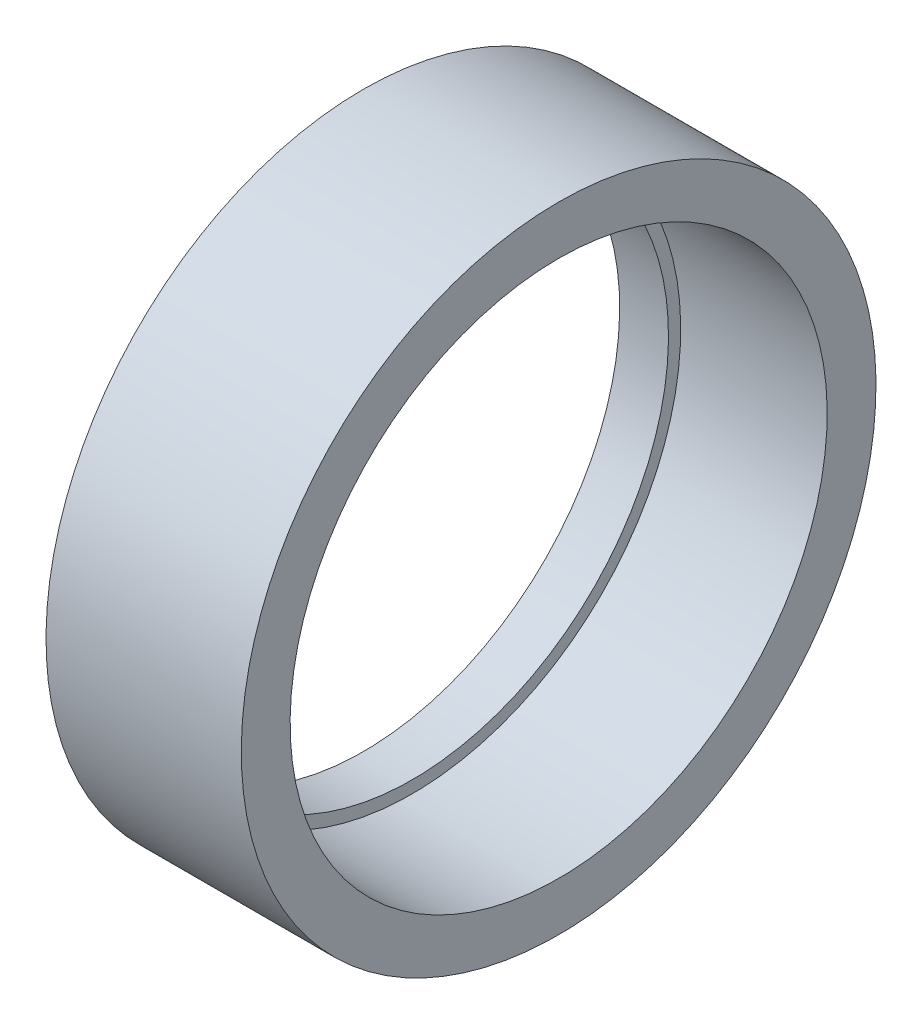
SolidWorks part; units mm, degrees
material "5052-H34"
ref_plane "Front Plane" through (0, 0, 0) normal (0, 0, 1) x (1, 0, 0)
ref_plane "Top Plane" through (0, 0, 0) normal (0, 1, 0) x (1, 0, 0)
ref_plane "Right Plane" through (0, 0, 0) normal (1, 0, 0) x (0, 0, -1)
sketch "Sketch2" plane through (0, 0, 0) normal (0, 0, 1) x (1, 0, 0)
  line L0 (0, 0) -> (0, 11) construction
  line L1 (0, 11) -> (0, 13)
  line L2 (0, 13) -> (-8, 13)
  line L3 (-8, 13) -> (-8, 10.5)
  line L4 (0, 11) -> (-6, 11)
  line L5 (-6, 11) -> (-6, 10.5)
  line L6 (0, 0) -> (-8, 0) construction
  line L7 (-8, 0) -> (-8, 10.5) construction
  line L8 (-6, 10.5) -> (-8, 10.5)
  dimension "D1" = 13
  dimension "D2" = 11
  dimension "D3" = 10.5
  dimension "D4" = 6
  dimension "D5" = 2
revolve "Revolve1" add sketch "Sketch2" angle 360 about L6
